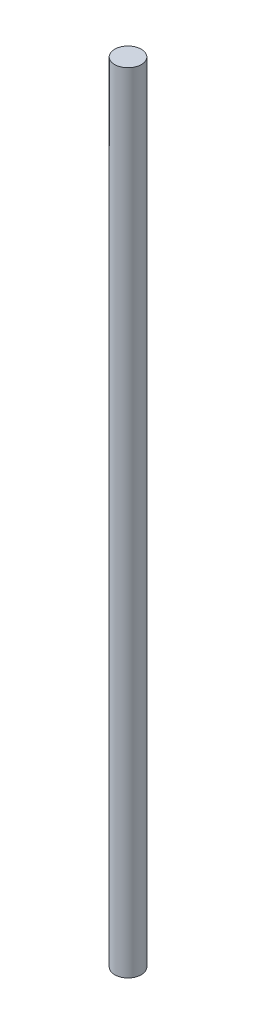
SolidWorks part; units mm, degrees
material "Nylon 101"
ref_plane "Alzado" through (0, 0, 0) normal (0, 0, 1) x (1, 0, 0)
ref_plane "Planta" through (0, 0, 0) normal (0, 1, 0) x (1, 0, 0)
ref_plane "Vista lateral" through (0, 0, 0) normal (1, 0, 0) x (0, 0, -1)
sketch "Sketch1" plane through (0, 0, 0) normal (0, 0, 1) x (1, 0, 0)
  line L0 (0, 0) -> (1.3, 0)
  line L1 (1.3, 0) -> (1.3, -77)
  line L2 (1.3, -77) -> (0, -77)
  line L3 (0, -77) -> (0, 0)
  line L4 (0, -81) -> (0, 4) construction
revolve "Tendon" add sketch "Sketch1" angle 360 about L4
